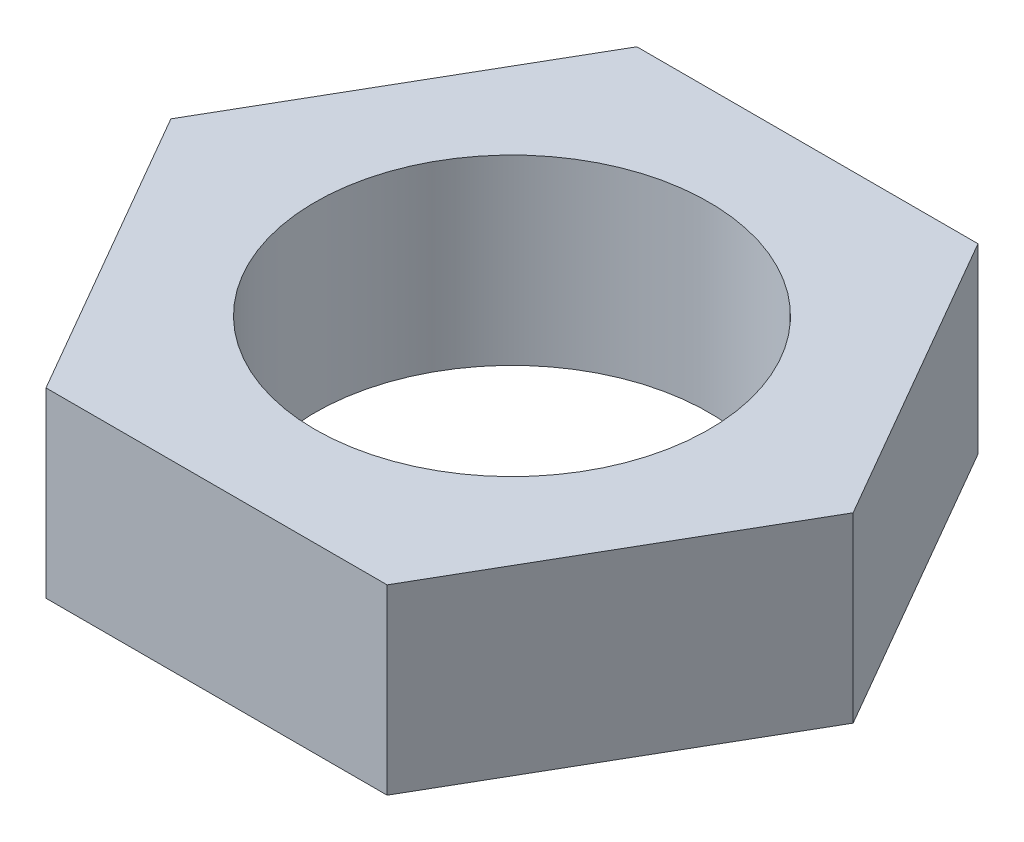
SolidWorks part; units mm, degrees
ref_plane "Front" through (0, 0, 0) normal (0, 0, 1) x (1, 0, 0)
ref_plane "Top" through (0, 0, 0) normal (0, 1, 0) x (1, 0, 0)
ref_plane "Right" through (0, 0, 0) normal (1, 0, 0) x (0, 0, -1)
sketch "Sketch1" plane through (0, 0, 0) normal (0, 1, 0) x (1, 0, 0)
  line L1 (3.4641, 0) -> (1.7321, 3)
  line L2 (1.7321, 3) -> (-1.7321, 3)
  line L3 (-1.7321, 3) -> (-3.4641, 0)
  line L4 (-3.4641, 0) -> (-1.7321, -3)
  line L5 (-1.7321, -3) -> (1.7321, -3)
  line L6 (1.7321, -3) -> (3.4641, 0)
  circle A0 centre (0, 0) radius 3 construction
  circle A1 centre (0, 0) radius 2
  point P10 (0, 2)
  dimension "D1" = 4
  dimension "D2" = 6
extrude "Boss-Extrude1" add sketch "Sketch1" along normal blind 1.85
